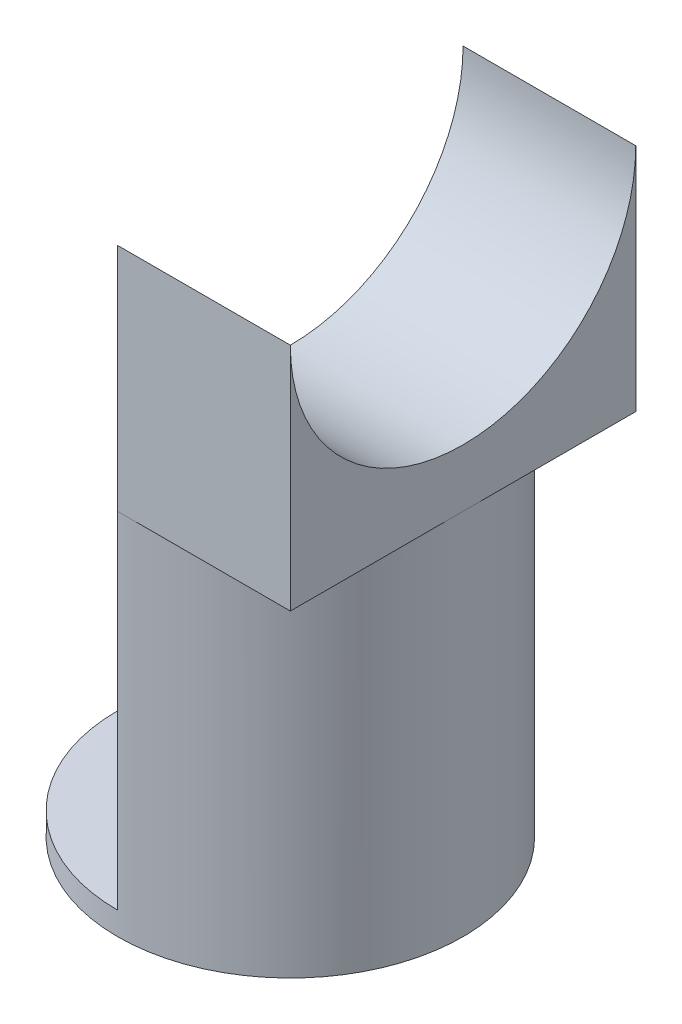
SolidWorks part; units mm, degrees
ref_plane "Front Plane" through (0, 0, 0) normal (0, 0, 1) x (1, 0, 0)
ref_plane "Top Plane" through (0, 0, 0) normal (0, 1, 0) x (1, 0, 0)
ref_plane "Right Plane" through (0, 0, 0) normal (1, 0, 0) x (0, 0, -1)
sketch "Sketch1" plane through (0, 0, 0) normal (0, 1, 0) x (1, 0, 0)
  circle A0 centre (0, 0) radius 75
  dimension "D1" = 150
extrude "Boss-Extrude1" add sketch "Sketch1" along normal blind 10
sketch "Sketch12" plane through (0, 10, 0) normal (0, 1, 0) x (1, 0, 0)
  line L0 (0, 0) -> (0, 75) construction
  line L1 (0, 75) -> (0, -75)
  circle A0 centre (0, 0) radius 75 construction
  arc A1 (0, -75) -> (0, 75) centre (0, 0) ccw
extrude "Boss-Extrude5" add sketch "Sketch12" along normal blind 150 contours L0 L1
sketch "Sketch13" plane through (0, 160, 0) normal (0, 1, 0) x (1, 0, 0)
  line L1 (0, 75) -> (75, 75)
  line L2 (0, 75) -> (0, -75)
  line L3 (0, -75) -> (75, -75)
  line L4 (75, 75) -> (75, -75)
extrude "Boss-Extrude6" add sketch "Sketch13" along normal blind 100
sketch "Sketch14" plane through (0, 0, 0) normal (-1, 0, 0) x (0, 0, 1)
  line L0 (-75, 260) -> (75, 260) construction
  circle A0 centre (0, 260) radius 75
extrude "Cut-Extrude5" cut sketch "Sketch14" against normal blind 100
